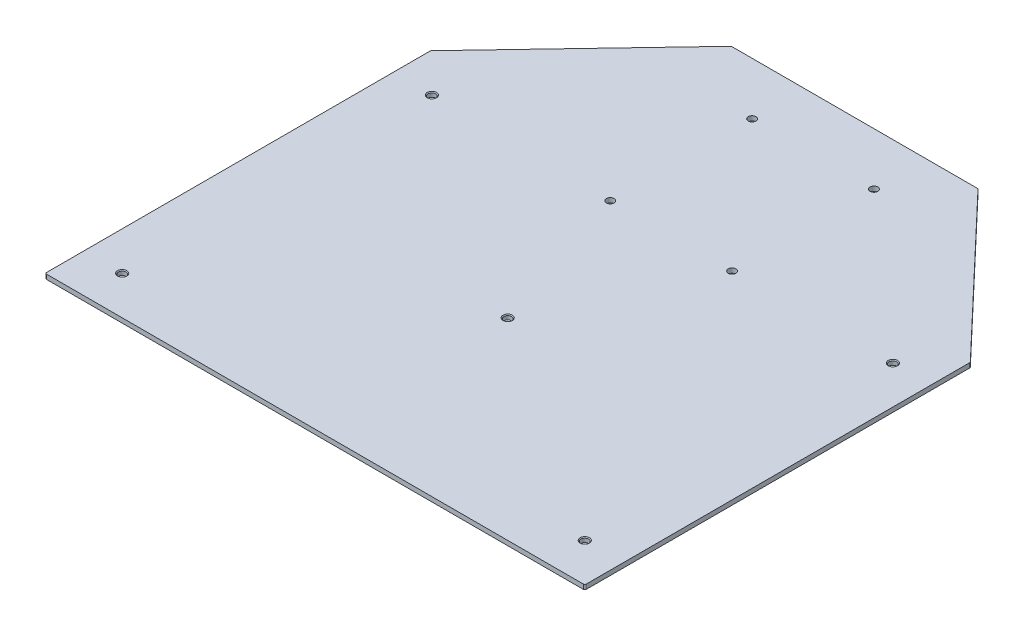
SolidWorks part; units mm, degrees
ref_plane "Front Plane" through (0, 0, 0) normal (0, 0, 1) x (1, 0, 0)
ref_plane "Top Plane" through (0, 0, 0) normal (0, 1, 0) x (1, 0, 0)
ref_plane "Right Plane" through (0, 0, 0) normal (1, 0, 0) x (0, 0, -1)
sketch "Plate Template" plane through (0, 0, 0) normal (0, 1, 0) x (1, 0, 0)
  line L0 (-79.5707, 225.0042) -> (79.5707, 225.0042)
  line L1 (-175, 125) -> (175, 125)
  line L2 (-175, 124.6007) -> (-175, -124)
  line L3 (-174, -125) -> (174, -125)
  line L4 (175, 124.6007) -> (175, -124)
  line L5 (-175, 125) -> (175, -125) construction
  line L6 (-175, -125) -> (175, 125) construction
  line L7 (-174.725, 125.2895) -> (-80.2957, 224.6929)
  line L8 (80.2957, 224.6929) -> (174.725, 125.2895)
  arc A0 (-174.725, 125.2895) -> (-175, 124.6007) centre (-174, 124.6007) ccw
  arc A1 (-175, -124) -> (-174, -125) centre (-174, -124) ccw
  arc A2 (175, -124) -> (174, -125) centre (174, -124) cw
  arc A3 (174.725, 125.2895) -> (175, 124.6007) centre (174, 124.6007) cw
  arc A4 (79.5707, 225.0042) -> (80.2957, 224.6929) centre (79.5707, 224.0042) cw
  arc A5 (-79.5707, 225.0042) -> (-80.2957, 224.6929) centre (-79.5707, 224.0042) ccw
  point P0 (0, 0)
  point P8 (0, 225.0042)
  point P9 (0, 125)
  point P24 (80, 225.0042)
  point P27 (-80, 225.0042)
  dimension "D5" = 1
  dimension "D1" = 350
  dimension "D2" = 250
  dimension "D3" = 160
  dimension "D4" = 136.47
extrude "Plate Extrude 1" add sketch "Plate Template" along normal blind 3 contours L7 A5 L0 A4 L8 A3 L4 A2 L3 A1 L2 A0
hole_wizard "M6 Tapped Hole2" positions "Sketch2" profile "Sketch3" tap size "M6" standard "ISO" end condition through all
sketch "Sketch2" plane through (0, 3, 0) normal (0, 1, 0) x (1, 0, 0)
  line L2 (-150, -100) -> (-150, -125)
  line L3 (-174, -125) -> (174, -125) construction
  line L4 (-150, -100) -> (150, -100)
  line L6 (-175, 124.6007) -> (-175, -124) construction
  line L7 (0, 0) -> (-175, 0.3004)
  line L9 (-149.6558, 100.5143) -> (150.3424, 99.4845)
  point P6 (-150, -100)
  point P15 (150, -100)
  point P20 (0, 0)
  point P27 (-149.6558, 100.5143)
  point P28 (150.3424, 99.4845)
  dimension "D1" = 25
  dimension "D2" = 300
  dimension "D3" = 25
sketch "Sketch3" plane through (-150, 3, 100) normal (1, 0, 0) x (0, 0, 1)
  line L0 (0, 0) -> (0, 3)
  line L1 (0, 3) -> (2.5, 3)
  line L2 (2.5, 3) -> (2.5, 0.525)
  line L3 (2.5, 0.525) -> (3.025, 0)
  line L5 (3.025, 0) -> (0, 0)
  line L6 (-2.5, 0.525) -> (-3.025, 0) construction
  line L11 (0, -6.35) -> (0, 107.95) construction
  dimension "Thru Tap Drill Dia." = 5
  dimension "Thru Tap Drill Depth" = 3
  dimension "Near C'Sink Dia." = 6.05
  dimension "Near C'Sink Angle" = 90
cosmetic thread "Hole Thread1" parameters "D2"=6
cosmetic thread "Hole Thread2" parameters "D2"=6
cosmetic thread "Hole Thread3" parameters "D2"=6
cosmetic thread "Hole Thread4" parameters "D2"=6
cosmetic thread "Hole Thread5" parameters "D2"=6
hole_wizard "Tap Drill for M6 Tap1" positions "Sketch4" profile "Sketch5" hole size "M6" standard "ISO"
sketch "Sketch4" plane through (0, 0, 0) normal (0, -1, 0) x (-1, 0, 0)
  line L0 (79.5707, 225.0042) -> (-79.5707, 225.0042) construction
  line L1 (175, 124.6007) -> (175, -124) construction
  point P0 (-46.5, 191.0042)
  point P3 (32.5, 191.0042)
  point P6 (32.5, 99.0042)
  point P9 (-46.5, 99.0042)
  point P14 (0, 0)
  point P15 (0, 0)
  point P16 (0, 0)
  point P17 (0, 0)
  point P18 (0, 0)
  dimension "D1" = 79
  dimension "D2" = 92
  dimension "D3" = 34
  dimension "D4" = 142.5
sketch "Sketch5" plane through (46.5, 0, -191.0042) normal (1, 0, 0) x (0, 0, -1)
  line L0 (0, 0) -> (0, 11.5022)
  line L1 (0, 11.5022) -> (2.5, 10)
  line L2 (2.5, 10) -> (2.5, 0.025)
  line L3 (2.5, 0.025) -> (2.525, 0)
  line L5 (2.525, 0) -> (0, 0)
  line L6 (-2.5, 0.025) -> (-2.525, 0) construction
  line L10 (0, 11.5022) -> (-2.5, 10) construction
  line L11 (0, -6.35) -> (0, 107.95) construction
  dimension "Hole Dia." = 5
  dimension "Hole Depth" = 10
  dimension "Near C'Sink Dia." = 5.05
  dimension "Near C'Sink Angle" = 90
  dimension "Drill Angle" = 118
